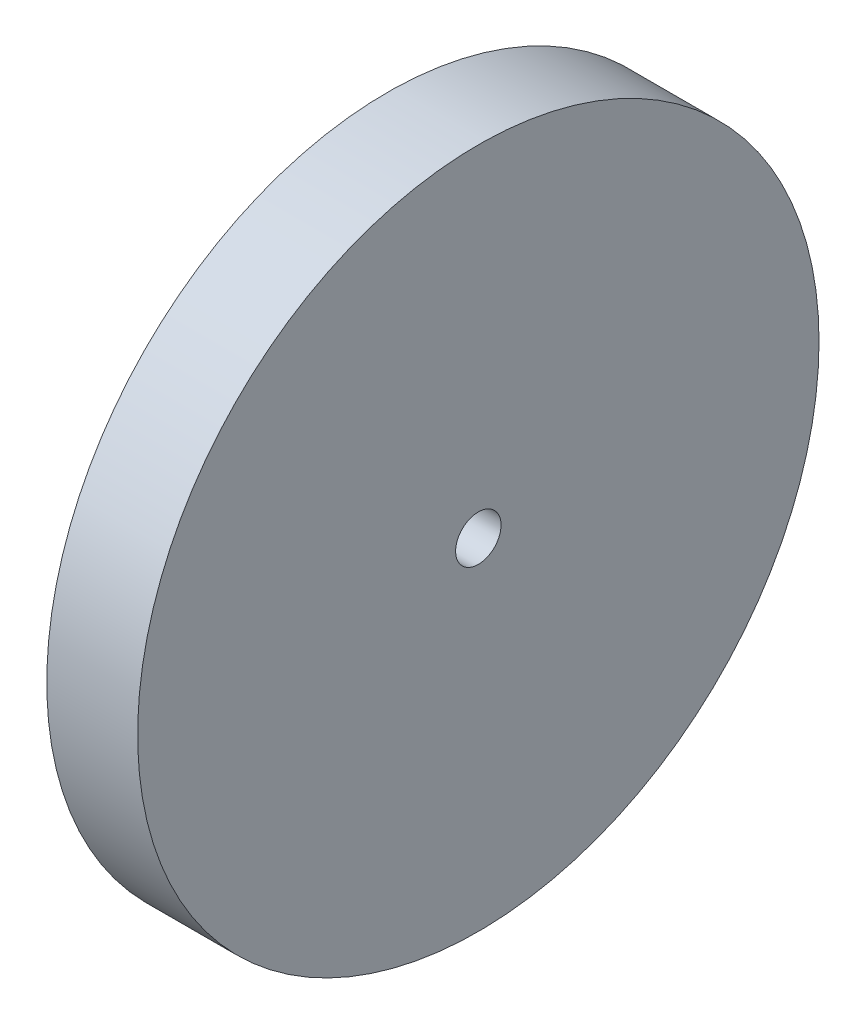
SolidWorks part; units mm, degrees
material "AISI 1020"
ref_plane "Plano frontal" through (0, 0, 0) normal (0, 0, 1) x (1, 0, 0)
ref_plane "Plano superior" through (0, 0, 0) normal (0, 1, 0) x (1, 0, 0)
ref_plane "Plano direito" through (0, 0, 0) normal (1, 0, 0) x (0, 0, -1)
sketch "Esboço3" plane through (0, 0, 0) normal (0, 0, 1) x (1, 0, 0)
  line L0 (0, 0) -> (-50.7324, 0) construction
  line L1 (0, 30) -> (0, 2)
  line L2 (0, 30) -> (-8, 30)
  line L3 (-8, 30) -> (-8, 5)
  line L4 (-8, 5) -> (-18, 5)
  line L5 (-18, 5) -> (-18, 2)
  line L6 (-18, 2) -> (0, 2)
  dimension "D1" = 2
  dimension "D2" = 30
  dimension "D3" = 8
  dimension "D4" = 10
  dimension "D5" = 5
revolve "Revolução1" add sketch "Esboço3" angle 360 about L0
ref_plane "Plano1" through (0, 5, 0) normal (0, 1, 0) x (1, 0, 0)
hole_wizard "Broca de rosquear para tarraxa de M2.2x0.451" positions "3DSketch6" profile "Esboço11" hole size "M2.2x0.45" standard "DIN"
sketch3d "3DSketch6"
  point P0 (-13.4532, 5, 0)
sketch "Esboço11" plane through (-13.4532, 5, 0) normal (1, 0, 0) x (0, 0, 1)
  line L0 (0, 0) -> (0, 3)
  line L1 (0, 3) -> (0.875, 3)
  line L2 (0.875, 3) -> (0.875, 0)
  line L5 (0.875, 0) -> (0, 0)
  line L11 (0, -6.35) -> (0, 107.95) construction
  dimension "Thru Hole Dia." = 1.75
  dimension "Thru Hole Depth" = 3
